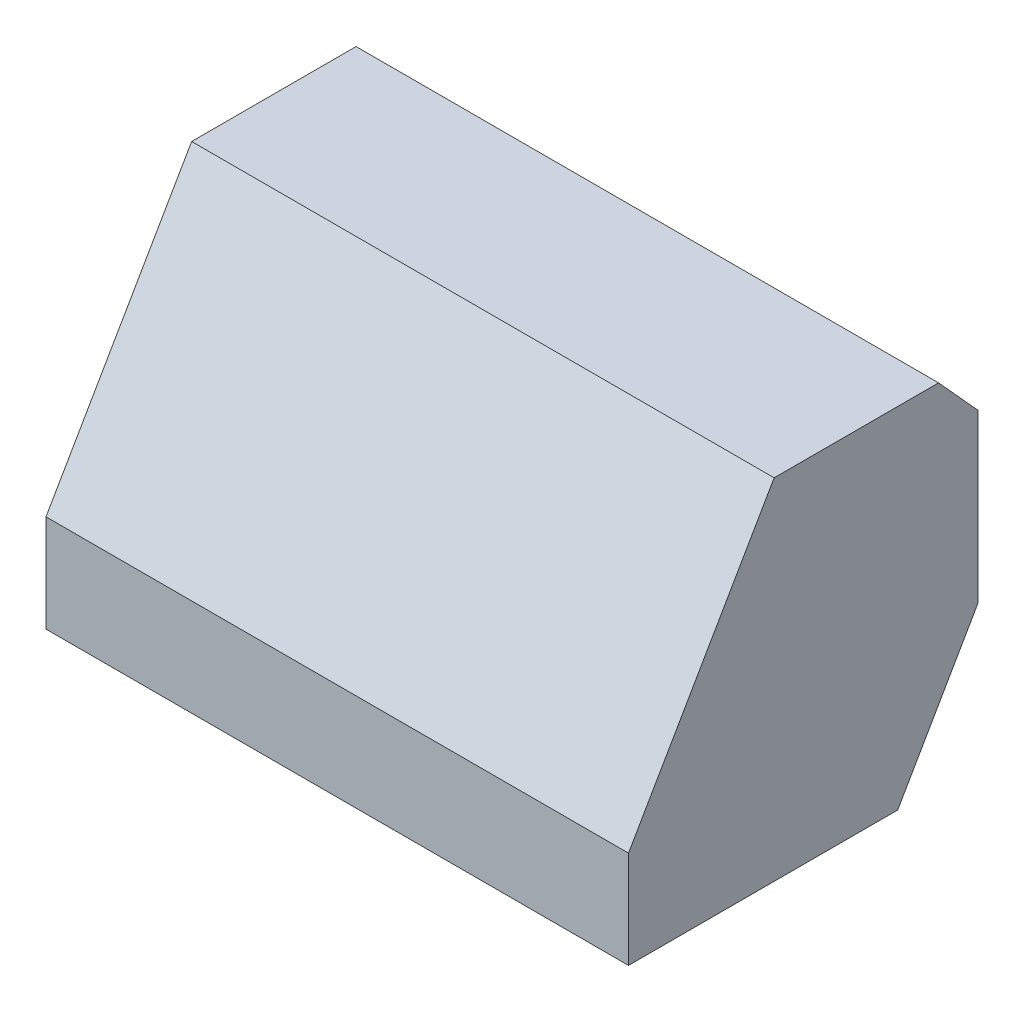
SolidWorks part; units mm, degrees
ref_plane "Front Plane" through (0, 0, 0) normal (0, 0, 1) x (1, 0, 0)
ref_plane "Top Plane" through (0, 0, 0) normal (0, 1, 0) x (1, 0, 0)
ref_plane "Right Plane" through (0, 0, 0) normal (1, 0, 0) x (0, 0, -1)
sketch "Sketch1" plane through (0, 0, 0) normal (0, 1, 0) x (1, 0, 0)
  line L1 (-50, 30) -> (50, 30)
  line L2 (-50, 30) -> (-50, -30)
  line L3 (-50, -30) -> (50, -30)
  line L4 (50, 30) -> (50, -30)
  line L5 (-50, 30) -> (50, -30) construction
  line L6 (-50, -30) -> (50, 30) construction
  point P0 (0, 0)
  dimension "D1" = 60
  dimension "D2" = 100
extrude "Boss-Extrude1" add sketch "Sketch1" along normal blind 60
sketch "Sketch2" plane through (50, 0, 0) normal (1, 0, 0) x (0, 0, -1)
  line L0 (-30, 60) -> (-30, 16.6987)
  line L1 (-30, 60) -> (-30, 0) construction
  line L2 (-30, 16.6987) -> (-5, 60)
  line L3 (-30, 60) -> (30, 60) construction
  line L4 (-5, 60) -> (-30, 60)
  line L5 (30, 0) -> (30, 23.8736)
  line L6 (30, 60) -> (30, 0) construction
  line L7 (30, 23.8736) -> (16.2166, 0)
  line L8 (-30, 0) -> (30, 0) construction
  line L9 (16.2166, 0) -> (30, 0)
  line L10 (23.2327, 60) -> (30, 60)
  line L11 (30, 60) -> (30, 52.5406)
  line L12 (30, 52.5406) -> (23.2327, 60)
  point P16 (30, 52.5406)
  dimension "D1" = 50
  dimension "D2" = 60
extrude "Cut-Extrude1" cut sketch "Sketch2" against normal up to surface (100 mm away) up to face at (-50, 30, 0)
